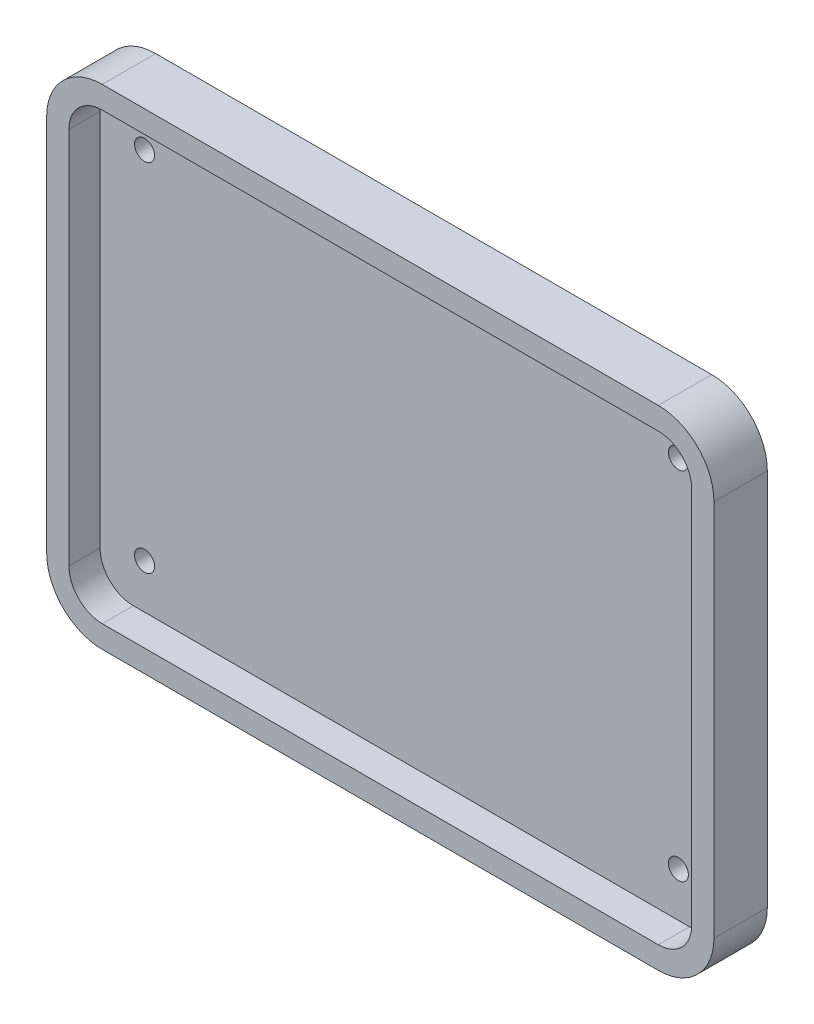
SolidWorks part; units mm, degrees
ref_plane "前视基准面" through (0, 0, 0) normal (0, 0, 1) x (1, 0, 0)
ref_plane "上视基准面" through (0, 0, 0) normal (0, 1, 0) x (1, 0, 0)
ref_plane "右视基准面" through (0, 0, 0) normal (1, 0, 0) x (0, 0, -1)
other "Configuration Table"
sketch "草图1" plane through (0, 0, 0) normal (0, 0, 1) x (1, 0, 0)
  line L0 (-75, 0) -> (75, 0) construction
  line L1 (-75, -55) -> (75, -55)
  line L2 (-75, -55) -> (-75, 55)
  line L3 (-75, 55) -> (75, 55)
  line L4 (75, -55) -> (75, 55)
  line L5 (-75, -55) -> (75, 55) construction
  line L6 (-75, 55) -> (75, -55) construction
  point P0 (0, 0)
  point P10 (0, 0)
  point P16 (0, 0)
  dimension "D1" = 150
  dimension "D2" = 110
extrude "凸台-拉伸1" add sketch "草图1" along normal blind 12
fillet "圆角1" radius 12.5 4 edges at (-75, -55, 6) (-75, 55, 6) (75, 55, 6) (75, -55, 6)
shell "抽壳1" thickness 5
sketch "草图3" plane through (0, 0, 5) normal (0, 0, 1) x (1, 0, 0)
  line L0 (-75, 42.5) -> (-75, -42.5) construction
  line L1 (-75, 0) -> (75, 0) construction
  line L2 (75, -42.5) -> (75, 42.5) construction
  circle A0 centre (-60, 40) radius 2.25
  circle A1 centre (60, 40) radius 2.25
  circle A2 centre (60, -40) radius 2.25
  circle A3 centre (-60, -40) radius 2.25
  point P10 (0, 0)
  dimension "D1" = 15
  dimension "D3" = 40
  dimension "D2" = 120
  dimension "D4" = 40
extrude "切除-拉伸1" cut sketch "草图3" against normal through all
